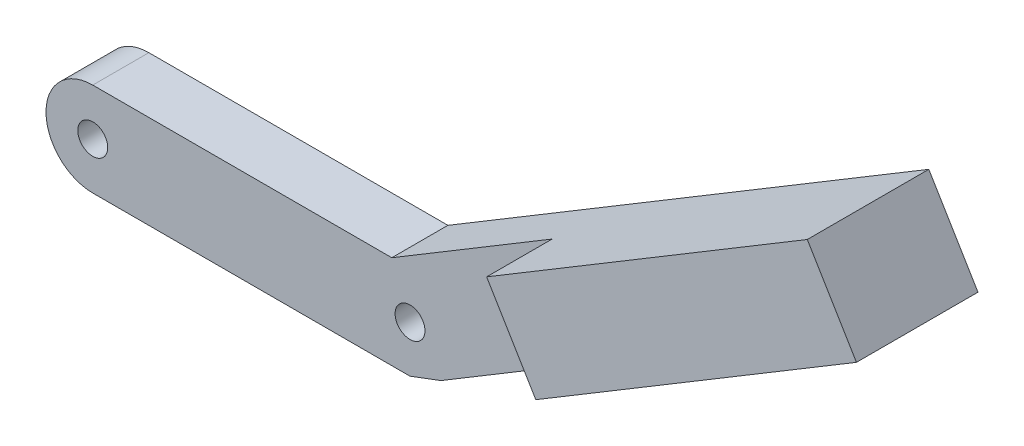
SolidWorks part; units mm, degrees
material "PLA"
ref_plane "Front Plane" through (0, 0, 0) normal (0, 0, 1) x (1, 0, 0)
ref_plane "Top Plane" through (0, 0, 0) normal (0, 1, 0) x (1, 0, 0)
ref_plane "Right Plane" through (0, 0, 0) normal (1, 0, 0) x (0, 0, -1)
sketch "Sketch1" plane through (0, 0, 0) normal (0, 0, 1) x (1, 0, 0)
  line L0 (0, 0) -> (33.93, 0) construction
  line L1 (0, 5) -> (33.93, 5)
  line L2 (0, -5) -> (33.93, -5)
  line L3 (31.98, 5) -> (37.2374, -3.7498) construction
  line L4 (31.98, 5) -> (83.41, 35.9023) construction
  line L5 (37.2374, -3.7498) -> (88.6675, 27.1525) construction
  line L6 (88.6675, 27.1525) -> (83.41, 35.9023)
  line L7 (31.98, 5) -> (83.41, 35.9023)
  line L8 (33.93, 0) -> (33.93, 29.9746) construction
  line L12 (88.6675, 27.1525) -> (37.2374, -3.7498)
  line L24 (37.2374, -3.7498) -> (33.93, -5)
  arc A0 (0, 5) -> (0, -5) centre (0, 0) ccw
  arc A1 (33.93, -5) -> (33.93, 5) centre (33.93, 0) ccw
  circle A2 centre (0, 0) radius 1.6
  circle A3 centre (33.93, 0) radius 1.6
  point P3 (16.965, 0)
  dimension "D2" = 10
  dimension "D11" = 3.2
  dimension "D1" = 33.93
  dimension "D3" = 149
  dimension "D4" = 1.95
  dimension "D5" = 60
extrude "Boss-Extrude1" add sketch "Sketch1" along normal blind 6
fillet "Fillet1" [suppressed] radius 1
sketch "Croquis3" plane through (0, 0, 6) normal (0, 0, 1) x (1, 0, 0)
  line L0 (83.41, 35.9023) -> (88.6675, 27.1525)
  line L1 (88.6675, 27.1525) -> (54.3808, 6.551)
  line L2 (88.6675, 27.1525) -> (37.2374, -3.7498) construction
  line L3 (54.3808, 6.551) -> (49.1233, 15.3008)
  line L4 (31.98, 5) -> (83.41, 35.9023) construction
  line L5 (49.1233, 15.3008) -> (83.41, 35.9023)
  dimension "D1" = 40
extrude "Saliente-Extruir1" add sketch "Croquis3" along normal blind 7
